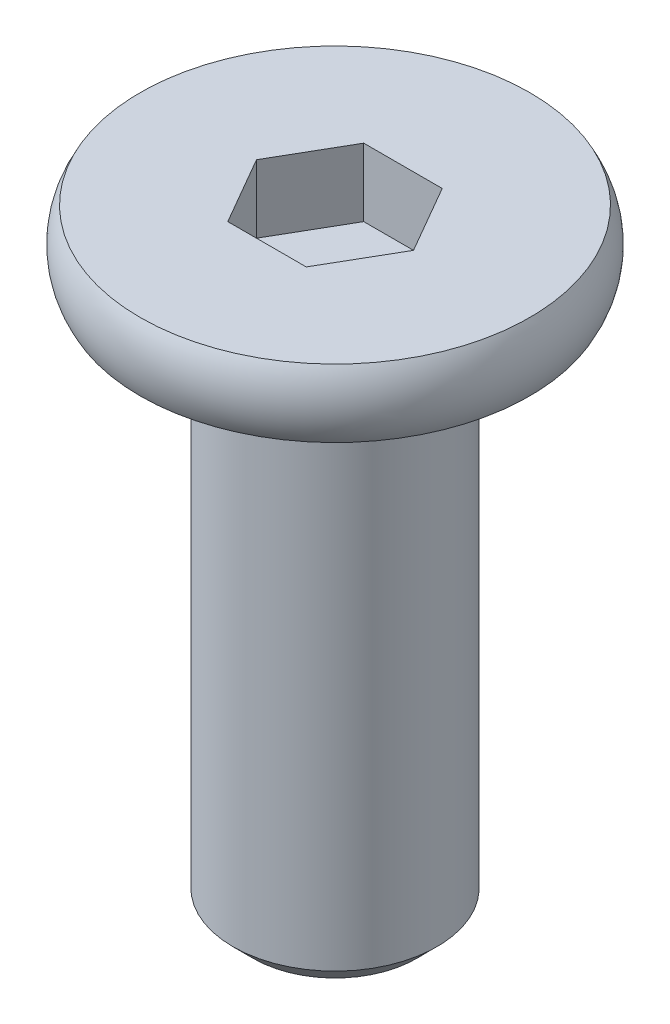
SolidWorks part; units mm, degrees
ref_plane "Front" through (0, 0, 0) normal (0, 0, 1) x (1, 0, 0)
ref_plane "Top" through (0, 0, 0) normal (0, 1, 0) x (1, 0, 0)
ref_plane "Right" through (0, 0, 0) normal (1, 0, 0) x (0, 0, -1)
sketch "草图1" plane through (0, 0, 0) normal (0, 0, 1) x (1, 0, 0)
  line L0 (0, 0) -> (0, -7.5914) construction
  line L1 (0, 0) -> (2.866, 0)
  line L3 (2.866, -1) -> (1.5, -1)
  line L4 (1.5, -1) -> (1.5, -9)
  line L5 (1.5, -9) -> (0, -9)
  line L6 (0, -9) -> (0, 0)
  line L7 (3, -0.5) -> (2, -0.5) construction
  arc A0 (2.866, -1) -> (2.866, 0) centre (2, -0.5) ccw
  dimension "D1" = 3
  dimension "D2" = 1
  dimension "D3" = 8
  dimension "D4" = 1.5
revolve "旋转1" add sketch "草图1" angle 360 about L0
chamfer "倒角1" distance 0.3 angle 45 1 edges at (0, -9, 1.5)
sketch "草图2" plane through (0, 0, 0) normal (0, 1, 0) x (1, 0, 0)
  line L1 (1.1547, 0) -> (0.5774, 1)
  line L2 (0.5774, 1) -> (-0.5774, 1)
  line L3 (-0.5774, 1) -> (-1.1547, 0)
  line L4 (-1.1547, 0) -> (-0.5774, -1)
  line L5 (-0.5774, -1) -> (0.5774, -1)
  line L6 (0.5774, -1) -> (1.1547, 0)
  circle A0 centre (0, 0) radius 1 construction
  dimension "D1" = 2
extrude "切除-拉伸1" cut sketch "草图2" against normal blind 1
